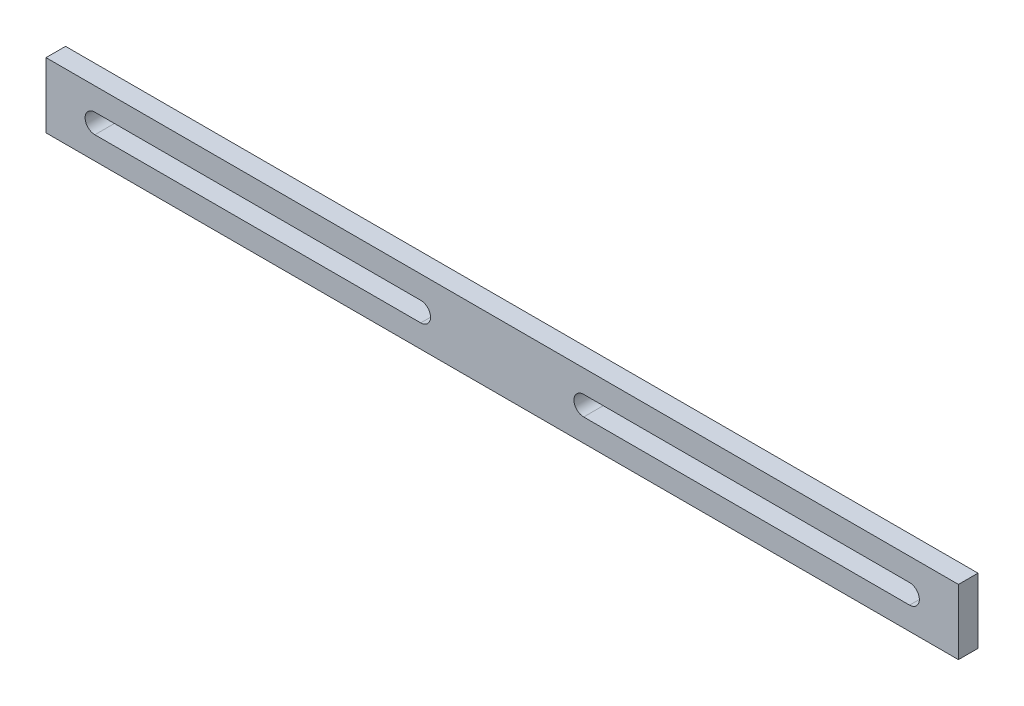
SolidWorks part; units mm, degrees
ref_plane "前视基准面" through (0, 0, 0) normal (0, 0, 1) x (1, 0, 0)
ref_plane "上视基准面" through (0, 0, 0) normal (0, 1, 0) x (1, 0, 0)
ref_plane "右视基准面" through (0, 0, 0) normal (1, 0, 0) x (0, 0, -1)
other "Configuration Table"
sketch "草图1" plane through (0, 0, 0) normal (0, 0, 1) x (1, 0, 0)
  line L0 (15, 10) -> (115, 10) construction
  line L1 (0, 0) -> (280, 0)
  line L2 (0, 0) -> (0, 20)
  line L3 (0, 20) -> (280, 20)
  line L4 (280, 0) -> (280, 20)
  line L5 (15, 13) -> (115, 13)
  line L6 (15, 7) -> (115, 7)
  line L8 (265, 10) -> (165, 10) construction
  line L9 (265, 13) -> (165, 13)
  line L10 (265, 7) -> (165, 7)
  arc A0 (15, 13) -> (15, 7) centre (15, 10) ccw
  arc A1 (115, 7) -> (115, 13) centre (115, 10) ccw
  arc A2 (265, 13) -> (265, 7) centre (265, 10) cw
  arc A3 (165, 7) -> (165, 13) centre (165, 10) cw
  point P4 (65, 10)
  point P13 (215, 10)
extrude "凸台-拉伸2" add sketch "草图1" along normal blind 6
